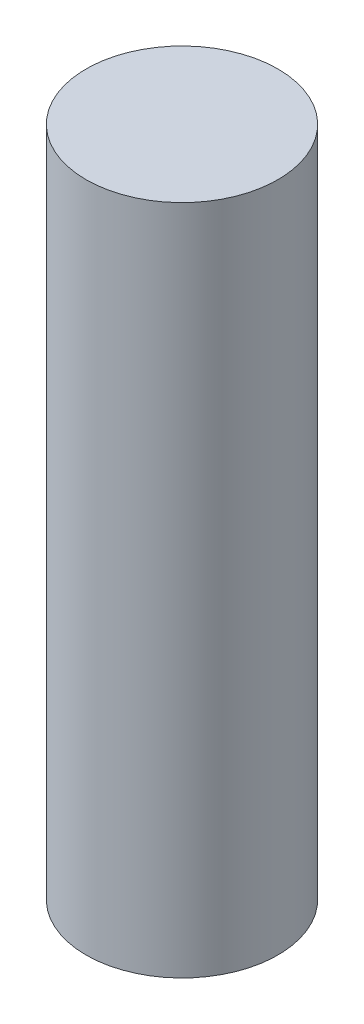
SolidWorks part; units mm, degrees
ref_plane "Front Plane" through (0, 0, 0) normal (0, 0, 1) x (1, 0, 0)
ref_plane "Top Plane" through (0, 0, 0) normal (0, 1, 0) x (1, 0, 0)
ref_plane "Right Plane" through (0, 0, 0) normal (1, 0, 0) x (0, 0, -1)
sketch "Sketch1" plane through (0, 0, 0) normal (0, 1, 0) x (1, 0, 0)
  circle A0 centre (0, 0) radius 2
  dimension "D1" = 4
extrude "Boss-Extrude1" add sketch "Sketch1" along normal mid plane 14
